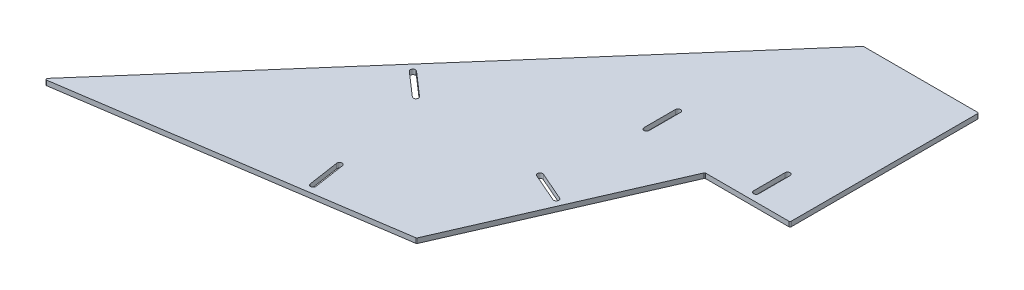
SolidWorks part; units mm, degrees
ref_plane "Front Plane" through (0, 0, 0) normal (1, 0, 0) x (0, 1, 0)
ref_plane "Top Plane" through (0, 0, 0) normal (0, 0, 1) x (0, 1, 0)
ref_plane "Right Plane" through (0, 0, 0) normal (0, 1, 0) x (-1, 0, 0)
sketch "Sketch2" plane through (0, 0, 0) normal (0, 1, 0) x (-1, 0, 0)
  line L1 (-4.6902, 155) -> (67.2472, 320)
  line L2 (67.2472, 320) -> (334.2678, 360)
  line L3 (334.2678, 360) -> (296.3473, 316.5613)
  line L4 (296.3473, 316.5613) -> (20, 0)
  line L5 (20, 0) -> (0, 0)
  line L6 (268.5042, 284.6665) -> (230.8374, 317.5483)
  line L7 (230.8374, 317.5483) -> (191.3792, 272.3481)
  line L8 (191.3792, 272.3481) -> (229.046, 239.4663)
  line L9 (-4.6902, 155) -> (-74.6902, 155)
  line L10 (-74.6902, 155) -> (-74.6902, 0)
  line L11 (-74.6902, 0) -> (0, 0)
  line L12 (-4.6902, 155) -> (155.3098, 155) construction
  line L13 (-39.6902, 147.9) -> (-39.6902, 122.1) construction
  line L14 (-41.7902, 147.9) -> (-41.7902, 122.1)
  line L15 (-37.5902, 147.9) -> (-37.5902, 122.1)
  line L16 (37.7868, 234.6625) -> (61.4368, 224.3514) construction
  line L17 (36.9476, 232.7375) -> (60.5976, 222.4264)
  line L18 (38.6261, 236.5875) -> (62.2761, 226.2764)
  line L19 (50.3098, 147.9) -> (50.3098, 122.1) construction
  line L20 (48.2098, 147.9) -> (48.2098, 122.1)
  line L21 (52.4098, 147.9) -> (52.4098, 122.1)
  line L22 (147.4163, 324.8302) -> (151.2385, 299.3149) construction
  line L23 (145.3395, 324.5191) -> (149.1617, 299.0038)
  line L24 (149.4931, 325.1413) -> (153.3153, 299.626)
  line L25 (168.0913, 219.6691) -> (187.5273, 202.7021) construction
  line L26 (166.7102, 218.0871) -> (186.1463, 201.1201)
  line L27 (169.4723, 221.2511) -> (188.9084, 204.2841)
  arc A0 (-41.7902, 147.9) -> (-37.5902, 147.9) centre (-39.6902, 147.9) cw
  arc A1 (-37.5902, 122.1) -> (-41.7902, 122.1) centre (-39.6902, 122.1) cw
  arc A2 (36.9476, 232.7375) -> (38.6261, 236.5875) centre (37.7868, 234.6625) cw
  arc A3 (62.2761, 226.2764) -> (60.5976, 222.4264) centre (61.4368, 224.3514) cw
  arc A4 (48.2098, 147.9) -> (52.4098, 147.9) centre (50.3098, 147.9) cw
  arc A5 (52.4098, 122.1) -> (48.2098, 122.1) centre (50.3098, 122.1) cw
  arc A6 (145.3395, 324.5191) -> (149.4931, 325.1413) centre (147.4163, 324.8302) cw
  arc A7 (153.3153, 299.626) -> (149.1617, 299.0038) centre (151.2385, 299.3149) cw
  arc A8 (166.7102, 218.0871) -> (169.4723, 221.2511) centre (168.0913, 219.6691) cw
  arc A9 (188.9084, 204.2841) -> (186.1463, 201.1201) centre (187.5273, 202.7021) cw
  point P16 (-39.6902, 135)
  point P23 (-39.6902, 155)
  point P28 (49.6118, 229.5069)
  point P35 (31.2785, 237.5)
  point P38 (50.3098, 135)
  point P49 (149.3274, 312.0725)
  point P57 (177.8093, 211.1856)
  dimension "D13" = 30
  dimension "D14" = 5
  dimension "D16" = 5
  dimension "D18" = 5
  dimension "D20" = 5
  dimension "D2" = 270
  dimension "D3" = 50
  dimension "D4" = 60
  dimension "D5" = 100
  dimension "D6" = 180
  dimension "D7" = 165
  dimension "D8" = 40
  dimension "D9" = 160
  dimension "D10" = 70
  dimension "D11" = 155
  dimension "D12" = 20
  dimension "D15" = 4.2
  dimension "D17" = 90
  dimension "D19" = 80
  dimension "D21" = 55
extrude "Boss-Extrude1" add sketch "Sketch2" along normal blind 4
fillet "Fillet1" radius 1 6 edges at (-20, 2, 0) (74.6902, 2, 0) (74.6902, 2, 155) (-334.2678, 2, 360) (4.6902, 2, 155) (-67.2472, 2, 320)
